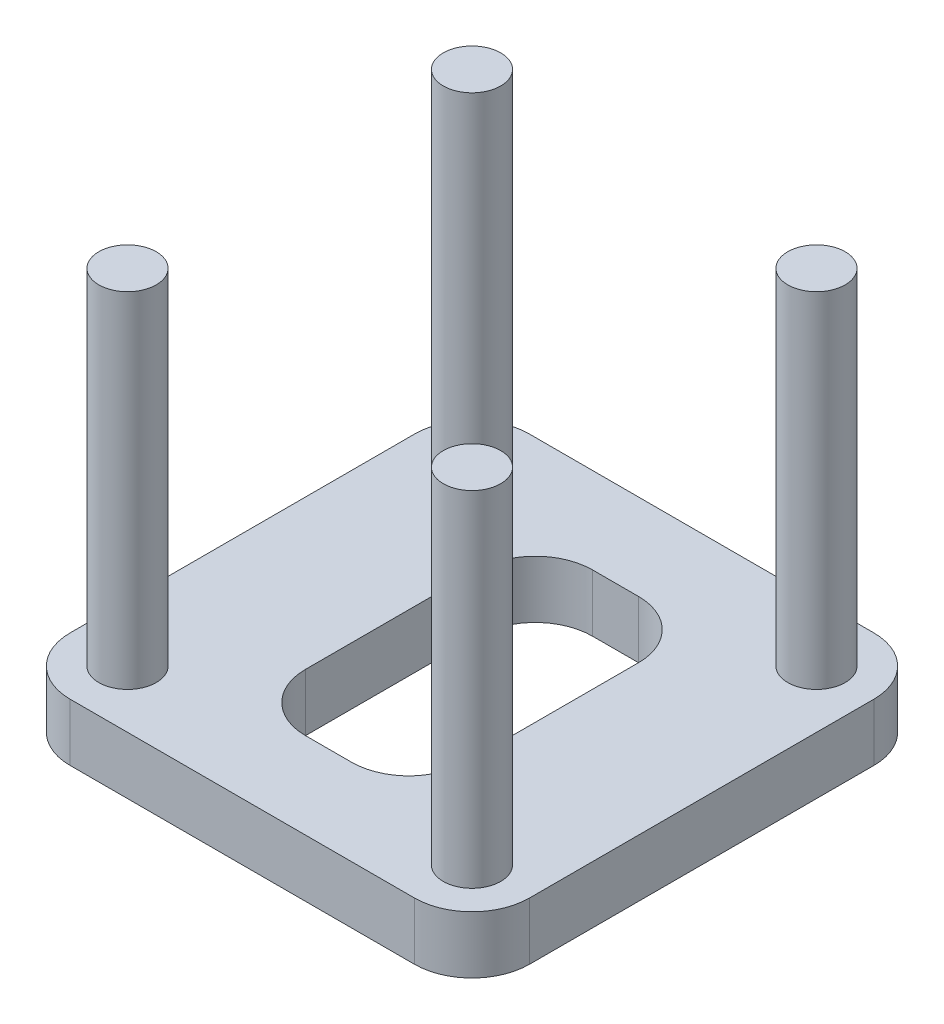
SolidWorks part; units mm, degrees
ref_plane "正面" through (0, 0, 0) normal (0, 0, 1) x (1, 0, 0)
ref_plane "平面" through (0, 0, 0) normal (0, 1, 0) x (1, 0, 0)
ref_plane "右側面" through (0, 0, 0) normal (1, 0, 0) x (0, 0, -1)
sketch "ｽｹｯﾁ1" plane through (0, 0, 0) normal (0, 1, 0) x (1, 0, 0)
  line L1 (-40, -40) -> (40, -40)
  line L2 (-40, -40) -> (-40, 40)
  line L3 (-40, 40) -> (40, 40)
  line L4 (40, -40) -> (40, 40)
  line L5 (-40, -40) -> (40, 40) construction
  line L6 (-40, 40) -> (40, -40) construction
  point P0 (0, 0)
  dimension "D1" = 80
extrude "ﾎﾞｽ - 押し出し1" add sketch "ｽｹｯﾁ1" along normal blind 10
fillet "ﾌｨﾚｯﾄ1" radius 10 4 edges at (-40, 5, -40) (40, 5, -40) (40, 5, 40) (-40, 5, 40)
sketch "ｽｹｯﾁ2" plane through (0, 0, 0) normal (0, 1, 0) x (1, 0, 0)
  line L0 (-40, 30) -> (-40, -30) construction
  line L1 (-32, 5) -> (-22, 5)
  line L2 (-32, 5) -> (-32, -5)
  line L3 (-32, -5) -> (-22, -5)
  line L4 (-22, 5) -> (-22, -5)
  line L5 (22, 5) -> (32, 5)
  line L6 (22, 5) -> (22, -5)
  line L7 (22, -5) -> (32, -5)
  line L8 (32, 5) -> (32, -5)
  line L9 (40, -30) -> (40, 30) construction
  point P8 (-22, 0)
  point P10 (22, 0)
  dimension "D1" = 8
  dimension "D2" = 10
  dimension "D3" = 8
extrude "ｶｯﾄ - 押し出し1" cut sketch "ｽｹｯﾁ2" along normal offset from surface (8 mm away) 2 up to face at (0, 10, 0)
sketch "ｽｹｯﾁ3" plane through (0, 10, 0) normal (0, 1, 0) x (1, 0, 0)
  line L0 (-40, 30) -> (-40, -30) construction
  line L1 (-4, -25) -> (4, -25)
  line L2 (-14, -15) -> (-14, 15)
  line L3 (-4, 25) -> (4, 25)
  line L4 (14, -15) -> (14, 15)
  line L5 (-14, -25) -> (14, 25) construction
  line L6 (-14, 25) -> (14, -25) construction
  arc A0 (4, -25) -> (14, -15) centre (4, -15) ccw
  arc A1 (-4, -25) -> (-14, -15) centre (-4, -15) cw
  arc A2 (4, 25) -> (14, 15) centre (4, 15) cw
  arc A3 (-14, 15) -> (-4, 25) centre (-4, 15) cw
  point P0 (0, 0)
  dimension "D1" = 26
  dimension "D3" = 10
  dimension "D2" = 50
extrude "ｶｯﾄ - 押し出し2" cut sketch "ｽｹｯﾁ3" against normal through all
sketch "ｽｹｯﾁ4" plane through (0, 10, 0) normal (0, 1, 0) x (1, 0, 0)
  circle A0 centre (-30, 30) radius 5
  circle A1 centre (30, 30) radius 5
  circle A2 centre (-30, -30) radius 5
  circle A3 centre (30, -30) radius 5
  arc A4 (-30, 40) -> (-40, 30) centre (-30, 30) ccw construction
  arc A5 (-40, -30) -> (-30, -40) centre (-30, -30) ccw construction
  arc A6 (30, -40) -> (40, -30) centre (30, -30) ccw construction
  arc A7 (40, 30) -> (30, 40) centre (30, 30) ccw construction
  dimension "D1" = 10
extrude "ﾎﾞｽ - 押し出し2" add sketch "ｽｹｯﾁ4" along normal blind 60
